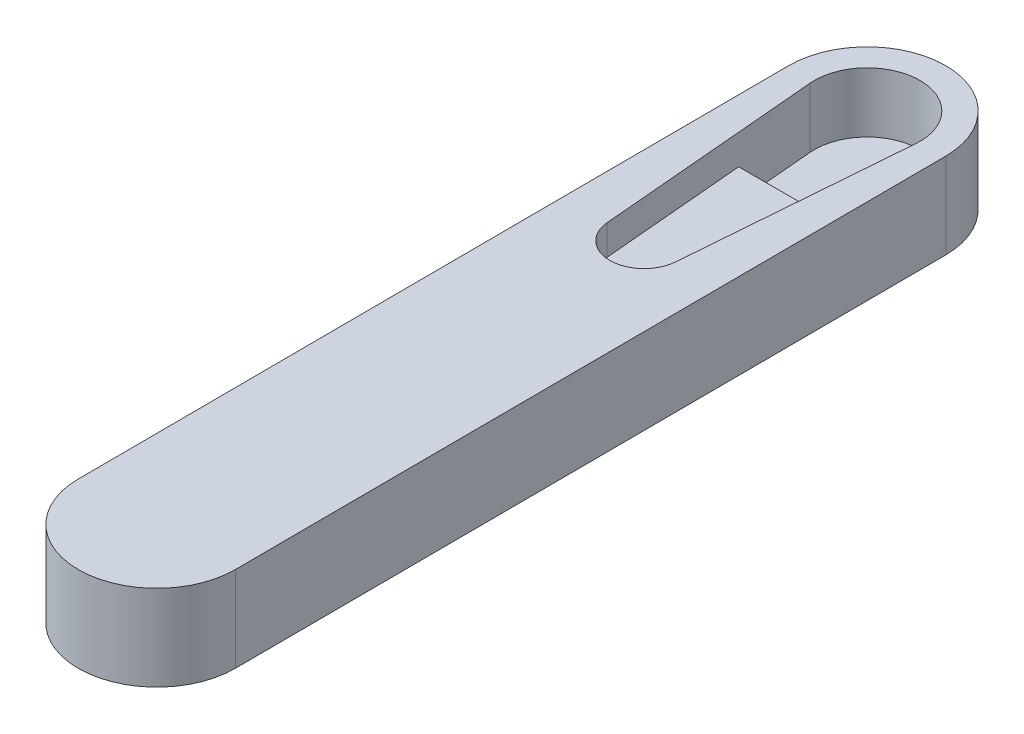
SolidWorks part; units mm, degrees
ref_plane "Спереди" through (0, 0, 0) normal (0, 0, 1) x (1, 0, 0)
ref_plane "Сверху" through (0, 0, 0) normal (0, 1, 0) x (1, 0, 0)
ref_plane "Справа" through (0, 0, 0) normal (1, 0, 0) x (0, 0, -1)
other "Configuration Table"
sketch "Эскиз2" plane through (0, 0, 0) normal (0, 1, 0) x (1, 0, 0)
  line L0 (-5.6963, 30.0104) -> (-5.4999, -19.9896)
  line L1 (5.3036, 30.0536) -> (5.5, -19.9464)
  arc A2 (-5.6963, 30.0104) -> (5.3036, 30.0536) centre (-0.1964, 30.032) cw
  arc A3 (-5.4999, -19.9896) -> (5.5, -19.9464) centre (0, -19.968) ccw
  dimension "D3" = 50
extrude "Бобышка-Вытянуть1" add sketch "Эскиз2" along normal blind 6
sketch "Эскиз3" plane through (0, 6, 0) normal (0, 1, 0) x (1, 0, 0)
  line L0 (-3.8824, 29.7111) -> (-2.5257, 14.1238)
  line L1 (3.4921, 29.7401) -> (2.2578, 14.1426)
  line L2 (5.5, -19.9464) -> (5.3036, 30.0536) construction
  arc A0 (-3.8824, 29.7111) -> (3.4921, 29.7401) centre (-0.1964, 30.032) cw
  arc A1 (-2.5257, 14.1238) -> (2.2578, 14.1426) centre (-0.1347, 14.332) ccw
  arc A2 (5.3036, 30.0536) -> (-5.6963, 30.0104) centre (-0.1964, 30.032) ccw construction
  point P7 (-0.1253, 11.932)
  point P12 (-0.218, 35.5319)
  point P13 (0, 0)
  point P14 (3.4864, 29.7111)
  point P17 (0, 0)
  dimension "D1" = 3.7
  dimension "D2" = 2.4
  dimension "D4" = 5.5
extrude "Вырез-Вытянуть1" cut sketch "Эскиз3" against normal blind 2.1
sketch "Эскиз4" plane through (0, 3.9, 0) normal (0, 1, 0) x (1, 0, 0)
  line L6 (-3.4055, 24.232) -> (3.0562, 24.232)
  line L7 (-3.8824, 29.7111) -> (-2.5257, 14.1238) construction
  line L8 (2.2578, 14.1426) -> (3.4921, 29.7401) construction
  line L11 (-3.8824, 29.7111) -> (-3.4055, 24.232)
  line L13 (3.4921, 29.7401) -> (3.0562, 24.232)
  arc A3 (-3.8824, 29.7111) -> (3.4921, 29.7401) centre (-0.1964, 30.032) cw
  arc A5 (3.4921, 29.7401) -> (-3.8824, 29.7111) centre (-0.1964, 30.032) ccw construction
  arc A6 (3.4921, 29.7401) -> (-3.8824, 29.7111) centre (-0.1964, 30.032) ccw construction
extrude "Вырез-Вытянуть2" cut sketch "Эскиз4" against normal blind 2.1
